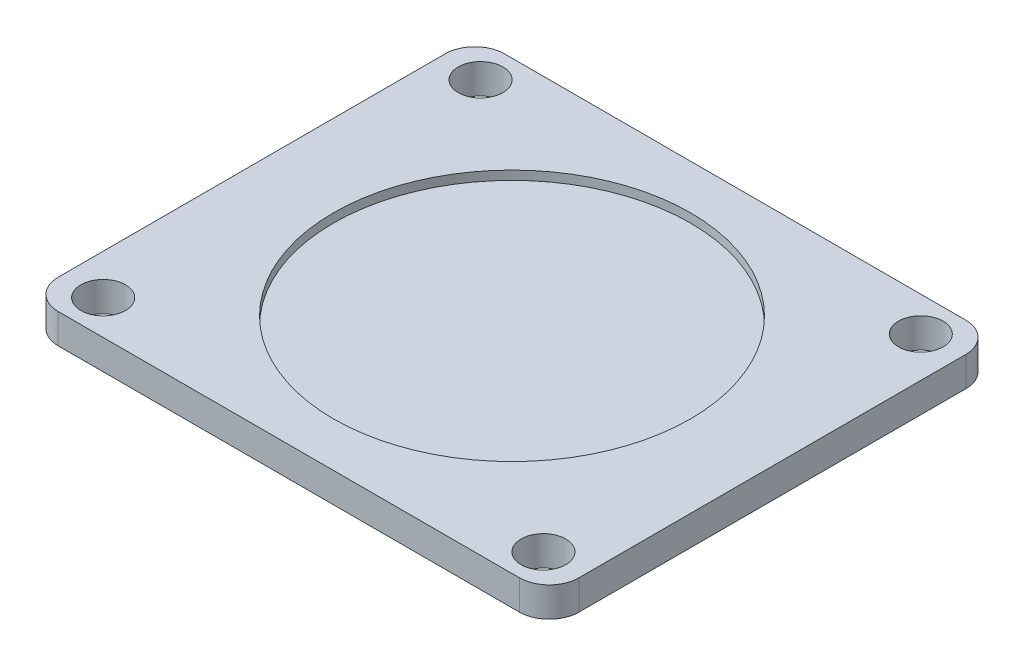
SolidWorks part; units mm, degrees
ref_plane "Front Plane" through (0, 0, 0) normal (0, 0, 1) x (1, 0, 0)
ref_plane "Top Plane" through (0, 0, 0) normal (0, 1, 0) x (1, 0, 0)
ref_plane "Right Plane" through (0, 0, 0) normal (1, 0, 0) x (0, 0, -1)
sketch "Sketch1" plane through (0, 0, 0) normal (0, 1, 0) x (1, 0, 0)
  line L1 (-15.5, 15) -> (15.5, 15)
  line L2 (-17.5, 13) -> (-17.5, -13)
  line L3 (-15.5, -15) -> (15.5, -15)
  line L4 (17.5, 13) -> (17.5, -13)
  line L5 (-17.5, 15) -> (17.5, -15) construction
  line L6 (-17.5, -15) -> (17.5, 15) construction
  line L7 (-14.7963, 12.6825) -> (14.7963, 12.6825) construction
  line L8 (-14.7963, 12.6825) -> (-14.7963, -12.6825) construction
  line L9 (-14.7963, -12.6825) -> (14.7963, -12.6825) construction
  line L10 (14.7963, 12.6825) -> (14.7963, -12.6825) construction
  line L11 (-14.7963, 12.6825) -> (14.7963, -12.6825) construction
  line L12 (-14.7963, -12.6825) -> (14.7963, 12.6825) construction
  arc A0 (15.5, -15) -> (17.5, -13) centre (15.5, -13) ccw
  arc A1 (-17.5, 13) -> (-15.5, 15) centre (-15.5, 13) cw
  arc A2 (-17.5, -13) -> (-15.5, -15) centre (-15.5, -13) ccw
  arc A3 (17.5, 13) -> (15.5, 15) centre (15.5, 13) ccw
  circle A4 centre (-14.7963, 12.6825) radius 1.5
  circle A5 centre (-14.7963, -12.6825) radius 1.5
  circle A6 centre (14.7963, 12.6825) radius 1.5
  circle A7 centre (14.7963, -12.6825) radius 1.5
  point P0 (0, 0)
  point P9 (0, 0)
  dimension "D3" = 2
  dimension "D4" = 2
  dimension "D5" = 2
  dimension "D1" = 35
  dimension "D2" = 30
extrude "Boss-Extrude2" add sketch "Sketch1" along normal blind 2
sketch "Sketch3" plane through (0, 0, 0) normal (0, -1, 0) x (1, 0, 0)
  circle A0 centre (0, 0) radius 12
extrude "Boss-Extrude3" add sketch "Sketch3" along normal blind 2
sketch "Sketch4" plane through (0, 0, 0) normal (1, 0, 0) x (0, 0, -1)
  line L1 (-12, 0) -> (-12, -2) construction
  line L2 (0, 0) -> (0, -5.7548) construction
  circle A1 centre (-12, -1.5) radius 0.5
  point P0 (-12, -1.5)
revolve "Revolve1" add sketch "Sketch4" angle 360 about L2
sketch "Sketch5" plane through (0, -2, 0) normal (0, -1, 0) x (1, 0, 0)
  circle A0 centre (0, 0) radius 2
extrude "Boss-Extrude4" add sketch "Sketch5" along normal blind 4.0407
fillet "Fillet1" radius 1 1 edges at (0, -6.0407, -2)
sketch "Sketch7" plane through (0, 2, 0) normal (0, 1, 0) x (1, 0, 0)
  circle A0 centre (0, 0) radius 12
extrude "Cut-Extrude3" cut sketch "Sketch7" against normal blind 0.6
